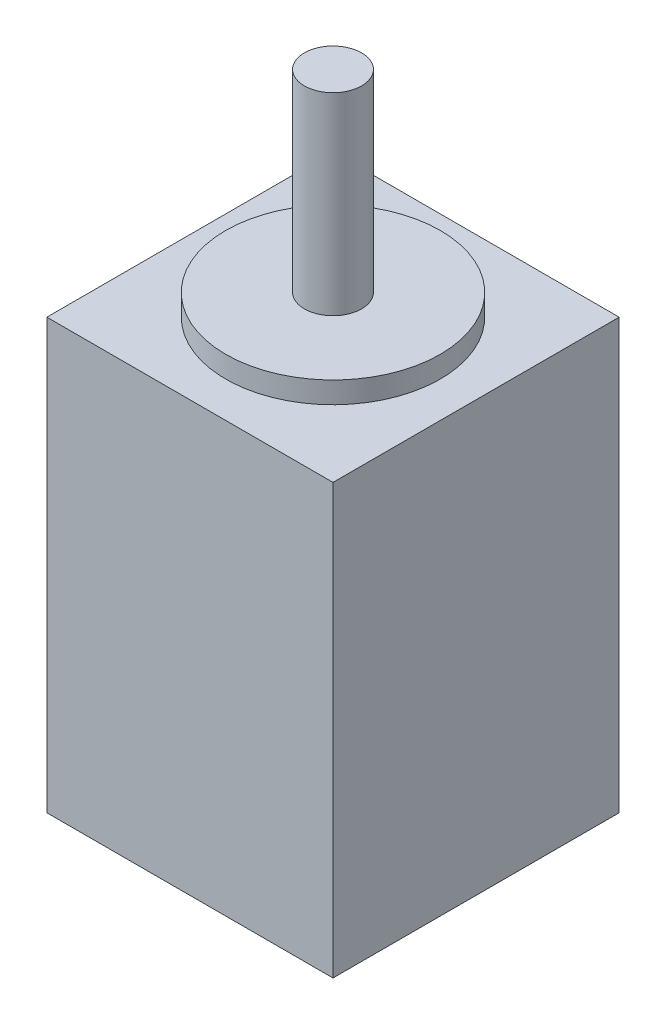
SolidWorks part; units mm, degrees
ref_plane "Front Plane" through (0, 0, 0) normal (0, 0, 1) x (1, 0, 0)
ref_plane "Top Plane" through (0, 0, 0) normal (0, 1, 0) x (1, 0, 0)
ref_plane "Right Plane" through (0, 0, 0) normal (1, 0, 0) x (0, 0, -1)
sketch "Sketch1" plane through (0, 0, 0) normal (0, 1, 0) x (1, 0, 0)
  line L1 (0, 0) -> (20, 0)
  line L2 (0, 0) -> (0, 20)
  line L3 (0, 20) -> (20, 20)
  line L4 (20, 0) -> (20, 20)
  dimension "D1" = 20
  dimension "D2" = 20
extrude "Boss-Extrude1" add sketch "Sketch1" along normal blind 30
sketch "Sketch2" plane through (0, 30, 0) normal (0, 1, 0) x (1, 0, 0)
  line L0 (0, 0) -> (20, 0) construction
  line L1 (0, 20) -> (0, 0) construction
  circle A0 centre (10, 10) radius 7.5
  dimension "D3" = 15
  dimension "D1" = 10
  dimension "D2" = 10
extrude "Boss-Extrude2" add sketch "Sketch2" along normal blind 1.5
sketch "Sketch3" plane through (0, 31.5, 0) normal (0, 1, 0) x (1, 0, 0)
  circle A0 centre (10, 10) radius 2
  dimension "D1" = 4
extrude "Boss-Extrude4" add sketch "Sketch3" along normal blind 13.5
